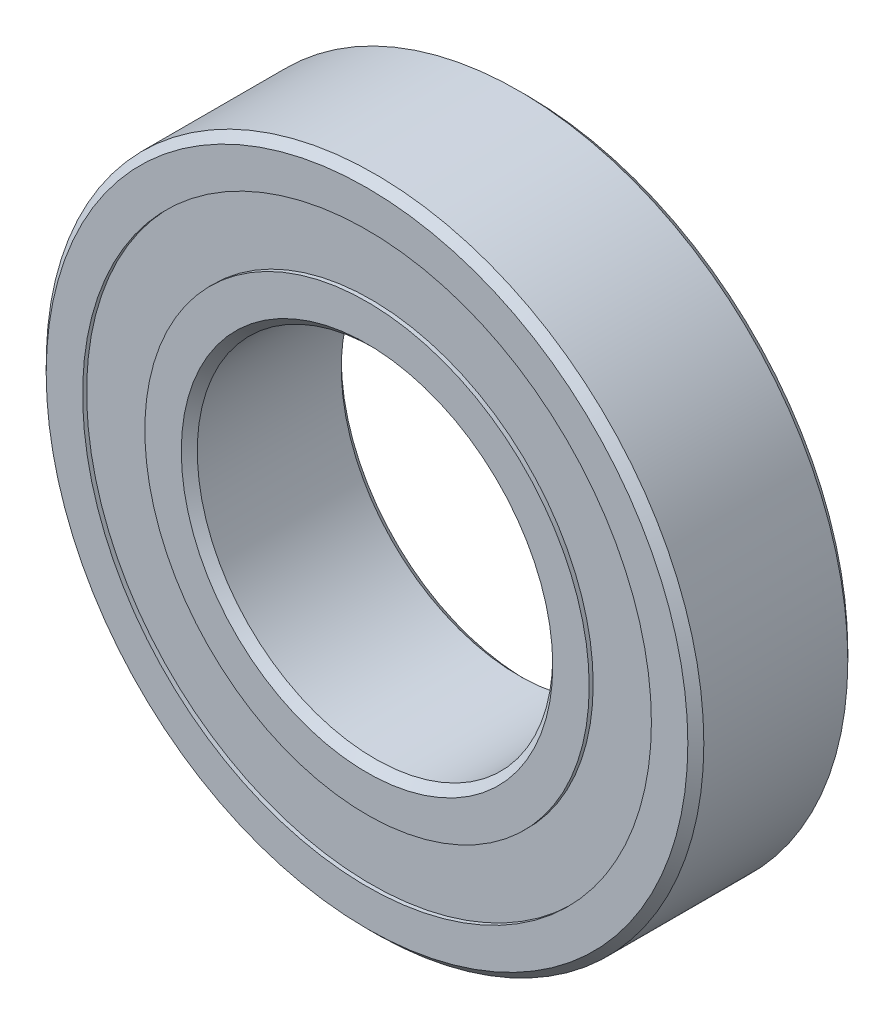
SolidWorks part; units mm, degrees
ref_plane "Front Plane" through (0, 0, 0) normal (0, 0, 1) x (1, 0, 0)
ref_plane "Top Plane" through (0, 0, 0) normal (0, 1, 0) x (1, 0, 0)
ref_plane "Right Plane" through (0, 0, 0) normal (1, 0, 0) x (0, 0, -1)
sketch "Sketch1" plane through (0, 0, 0) normal (0, 0, 1) x (1, 0, 0)
  circle A0 centre (0, 0) radius 18.5 construction
  circle A1 centre (0, 0) radius 10 construction
  dimension "OD" = 37
  dimension "ID" = 20
sketch "Sketch2" plane through (0, 0, 0) normal (1, 0, 0) x (0, 0, -1)
  line L0 (-4.5, 0) -> (4.5, 0) construction
  line L1 (0, 18.5) -> (0, -18.5) construction
  line L2 (4.05, 18.5) -> (-4.05, 18.5) construction
  line L3 (-4.05, 18.5) -> (-4.5, 18.05) construction
  line L4 (-4.5, 18.05) -> (-4.5, 16) construction
  line L5 (-4.5, 16) -> (-2, 16) construction
  line L6 (4.5, 16) -> (2, 16) construction
  line L7 (4.5, 18.05) -> (4.5, 16) construction
  line L8 (4.05, 18.5) -> (4.5, 18.05) construction
  line L9 (0, 18.5) -> (0, 14.25) construction
  line L10 (0, 14.25) -> (0, 10) construction
  line L11 (4.5, 14.25) -> (-4.5, 14.25) construction
  line L12 (-4.5, 10.45) -> (-4.5, 12.5) construction
  line L13 (-4.05, 10) -> (-4.5, 10.45) construction
  line L14 (4.05, 10) -> (-4.05, 10) construction
  line L15 (4.05, 10) -> (4.5, 10.45) construction
  line L16 (4.5, 10.45) -> (4.5, 12.5) construction
  line L17 (4.5, 12.5) -> (2, 12.5) construction
  line L18 (-4.5, 12.5) -> (-2, 12.5) construction
  line L19 (-4.5, 10) -> (-4.5, -10) construction
  line L20 (4.5, 18.5) -> (4.5, -18.5) construction
  arc A0 (-2, 16) -> (2, 16) centre (0, 14.25) cw construction
  arc A1 (-2, 12.5) -> (2, 12.5) centre (0, 14.25) ccw construction
  point P14 (0, 10)
  point P18 (0, 14.25)
  dimension "Approx. Ball Dia." = 5.3151
  dimension "D1" = 45
  dimension "D2" = 0.45
  dimension "D3" = 4
  dimension "D4" = 1.75
  dimension "Width" = 9
  dimension "For Shaft Diameter" = 20
  dimension "For Housing ID" = 37
sketch "Sketch3" plane through (0, 0, 0) normal (1, 0, 0) x (0, 0, -1)
  line L0 (-4.5, 18.05) -> (-4.5, 16) construction
  line L1 (-4.05, 18.5) -> (-4.5, 18.05) construction
  line L2 (4.05, 18.5) -> (-4.05, 18.5) construction
  line L3 (4.05, 18.5) -> (4.5, 18.05) construction
  line L4 (4.5, 18.05) -> (4.5, 16) construction
  line L5 (4.5, 16) -> (2, 16) construction
  line L6 (-4.5, 16) -> (-2, 16) construction
  line L7 (-4.5, 18.05) -> (-4.5, 16)
  line L8 (-4.05, 18.5) -> (-4.5, 18.05)
  line L9 (4.05, 18.5) -> (-4.05, 18.5)
  line L10 (4.05, 18.5) -> (4.5, 18.05)
  line L11 (4.5, 18.05) -> (4.5, 16)
  line L12 (4.5, 16) -> (2, 16)
  line L13 (-4.5, 16) -> (-2, 16)
  line L14 (-4.5, 10.45) -> (-4.5, 12.5) construction
  line L15 (-4.05, 10) -> (-4.5, 10.45) construction
  line L16 (4.05, 10) -> (-4.05, 10) construction
  line L17 (4.05, 10) -> (4.5, 10.45) construction
  line L18 (4.5, 10.45) -> (4.5, 12.5) construction
  line L19 (4.5, 12.5) -> (2, 12.5) construction
  line L20 (-4.5, 12.5) -> (-2, 12.5) construction
  line L21 (-4.5, 10.45) -> (-4.5, 12.5)
  line L22 (-4.05, 10) -> (-4.5, 10.45)
  line L23 (4.05, 10) -> (-4.05, 10)
  line L24 (4.05, 10) -> (4.5, 10.45)
  line L25 (4.5, 10.45) -> (4.5, 12.5)
  line L26 (4.5, 12.5) -> (2, 12.5)
  line L27 (-4.5, 12.5) -> (-2, 12.5)
  arc A0 (2, 16) -> (-2, 16) centre (0, 14.25) ccw construction
  arc A1 (2, 16) -> (-2, 16) centre (0, 14.25) ccw
  arc A2 (-2, 12.5) -> (2, 12.5) centre (0, 14.25) ccw construction
  arc A3 (-2, 12.5) -> (2, 12.5) centre (0, 14.25) ccw
revolve "Revolve1" add sketch "Sketch3" angle 360 about L0
sketch "Sketch4" plane through (0, 0, 0) normal (1, 0, 0) x (0, 0, -1)
  line L0 (-2.6575, 14.25) -> (2.6575, 14.25)
  arc A2 (-2.6575, 14.25) -> (2.6575, 14.25) centre (0, 14.25) cw
  arc A3 (2, 16) -> (-2, 16) centre (0, 14.25) ccw construction
revolve "Revolve2" add sketch "Sketch4" angle 360 about L0
pattern_circular "CirPattern1" count 11 over 360 about axis through (0, 0, 0) along (0, 0, 1) of bodies 104
sketch "Sketch5" plane through (0, 0, 0) normal (1, 0, 0) x (0, 0, -1)
  line L0 (-4.5, 16) -> (-2, 16) construction
  line L1 (-4.275, 16) -> (-2.6575, 16)
  line L2 (-4.275, 16) -> (-4.275, 12.5)
  line L3 (-4.275, 12.5) -> (-2.6575, 12.5)
  line L4 (-2.6575, 16) -> (-2.6575, 12.5)
  line L6 (4.5, 16) -> (2, 16) construction
  line L7 (4.275, 16) -> (2.6575, 16)
  line L8 (4.275, 16) -> (4.275, 12.5)
  line L9 (4.275, 12.5) -> (2.6575, 12.5)
  line L10 (2.6575, 16) -> (2.6575, 12.5)
  line L12 (-4.05, 18.5) -> (-4.5, 18.05) construction
  line L13 (-4.5, 12.5) -> (-2, 12.5) construction
  line L14 (4.5, 12.5) -> (2, 12.5) construction
  point P18 (-4.275, 18.275)
revolve "Revolve3" add sketch "Sketch5" angle 360 about L0
equation "\"D2@Sketch2\"= \"Width@Sketch2\" * .05"
equation "\"D3@Sketch2\"=\"Width@Sketch2\" / 2.25"
equation "\"D4@Sketch2\"=( \"OD@Sketch1\" - \"Width@Sketch2\" ) *.5 *.125"
equation "\"Approx. No. of Balls\"= ( pi * \"OD@Sketch1\" ) * .5 / \"Approx. Ball Dia.@Sketch2\""
equation "\"Balls@CirPattern1\"=\"Approx. No. of Balls\""
